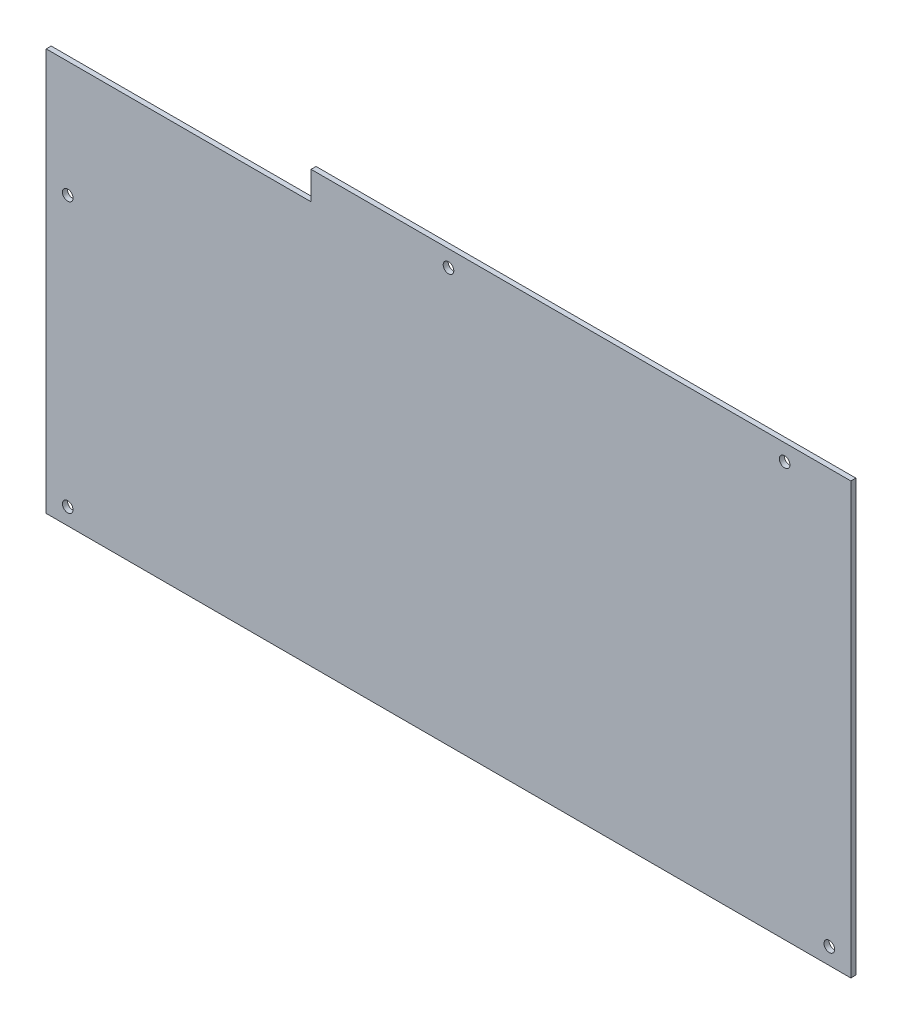
SolidWorks part; units mm, degrees
ref_plane "Front Plane" through (0, 0, 0) normal (0, 0, 1) x (1, 0, 0)
ref_plane "Top Plane" through (0, 0, 0) normal (0, 1, 0) x (1, 0, 0)
ref_plane "Right Plane" through (0, 0, 0) normal (1, 0, 0) x (0, 0, -1)
sketch "Sketch1" plane through (0, 0, 0) normal (0, 0, 1) x (1, 0, 0)
  line L0 (-241.5, -120) -> (1.5, -120)
  line L1 (1.5, -120) -> (1.5, 10)
  line L2 (1.5, 10) -> (-161.5, 10)
  line L3 (-161.5, 40) -> (-161.5, 1.5) construction
  line L4 (-161.5, 10) -> (-161.5, 1.5)
  line L5 (-161.5, 1.5) -> (-241.5, 1.5)
  line L6 (-241.5, -120) -> (-241.5, 21.5) construction
  line L7 (-241.5, 1.5) -> (-241.5, -120)
extrude "Boss-Extrude1" add sketch "Sketch1" along normal blind 1.5
sketch "Sketch2" plane through (0, 0, 1.5) normal (0, 0, 1) x (1, 0, 0)
  line L0 (-120, -120) -> (-120, 17.2737) construction
  line L1 (-241.5, -120) -> (1.5, -120) construction
  line L2 (1.5, 10) -> (-161.5, 10) construction
  line L3 (1.5, -120) -> (1.5, 10) construction
  circle A0 centre (-235, -33.5) radius 1.6
  circle A1 centre (-235, -115) radius 1.6
  circle A2 centre (-5, -115) radius 1.6
  circle A3 centre (-120, 5) radius 1.6
  circle A4 centre (-18.5, 5) radius 1.6
  dimension "D1" = 3.2
  dimension "D2" = 3.2
  dimension "D3" = 3.2
  dimension "D4" = 3.2
  dimension "D7" = 3.2
  dimension "D5" = 5
  dimension "D6" = 20
  dimension "D8" = 5
extrude "Cut-Extrude1" cut sketch "Sketch2" against normal blind 1.5
